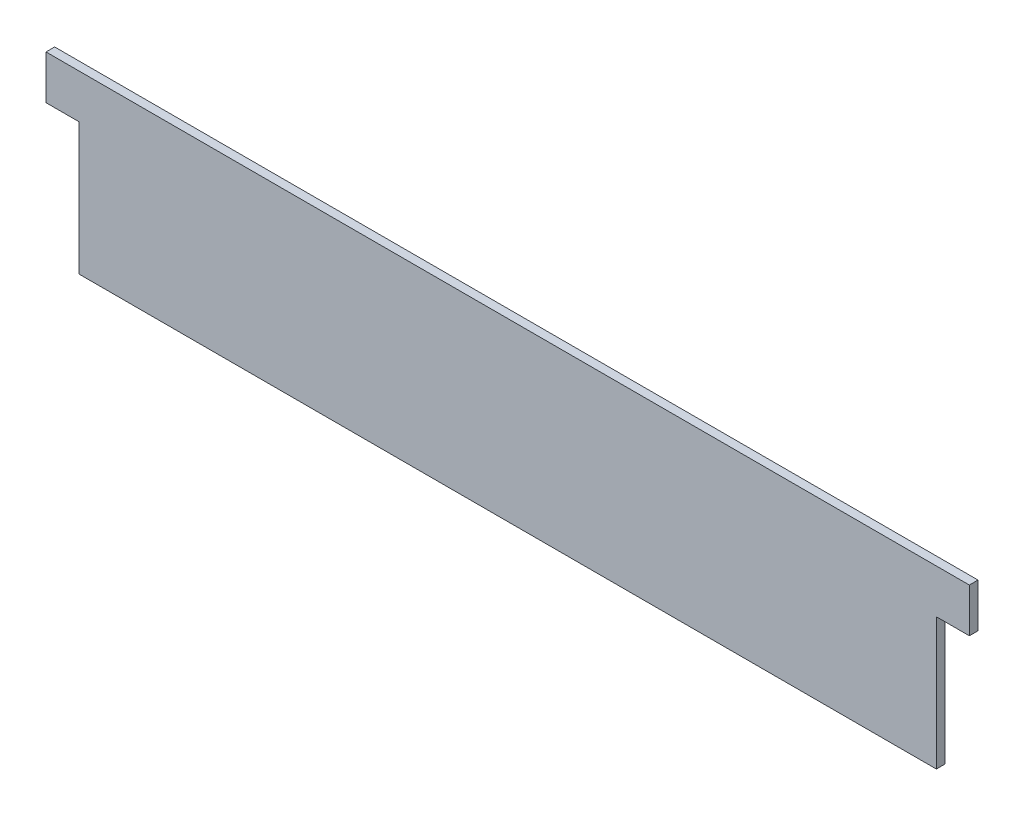
SolidWorks part; units mm, degrees
material "Oak"
ref_plane "Front Plane" through (0, 0, 0) normal (0, 0, 1) x (1, 0, 0)
ref_plane "Top Plane" through (0, 0, 0) normal (0, 1, 0) x (1, 0, 0)
ref_plane "Right Plane" through (0, 0, 0) normal (1, 0, 0) x (0, 0, -1)
sketch "Sketch1" plane through (0, 0, 0) normal (0, 0, 1) x (1, 0, 0)
  line L0 (-266.7, 63.5) -> (266.7, 63.5)
  line L1 (266.7, 63.5) -> (266.7, 38.1)
  line L2 (266.7, 38.1) -> (247.65, 38.1)
  line L3 (247.65, 38.1) -> (247.65, -38.1)
  line L4 (247.65, -38.1) -> (-247.65, -38.1)
  line L5 (-247.65, -38.1) -> (-247.65, 38.1)
  line L6 (-247.65, 38.1) -> (-266.7, 38.1)
  line L7 (-266.7, 38.1) -> (-266.7, 63.5)
  point P3 (0, 63.5)
  point P12 (-247.65, 0)
  dimension "D1" = 25.4
  dimension "D2" = 533.4
  dimension "D3" = 495.3
  dimension "D4" = 76.2
extrude "Boss-Extrude1" add sketch "Sketch1" along normal mid plane 5
sketch "Sketch2" plane through (0, 0, 2.5) normal (0, 0, 1) x (1, 0, 0)
  line L0 (-247.65, -38.1) -> (247.65, -38.1) construction
  line L1 (-6.35, 1.5875) -> (6.35, 1.5875)
  line L2 (-6.35, 1.5875) -> (-6.35, -3.175)
  line L3 (-6.35, -3.175) -> (6.35, -3.175)
  line L4 (6.35, 1.5875) -> (6.35, -3.175)
  line L5 (-6.35, 1.5875) -> (6.35, -3.175) construction
  line L6 (-6.35, -3.175) -> (6.35, 1.5875) construction
  point P0 (0, -0.7938)
  dimension "D1" = 4.7625
  dimension "D2" = 12.7
  dimension "D3" = 34.925
extrude "Cut-Extrude1" [suppressed] cut sketch "Sketch2" against normal through all
